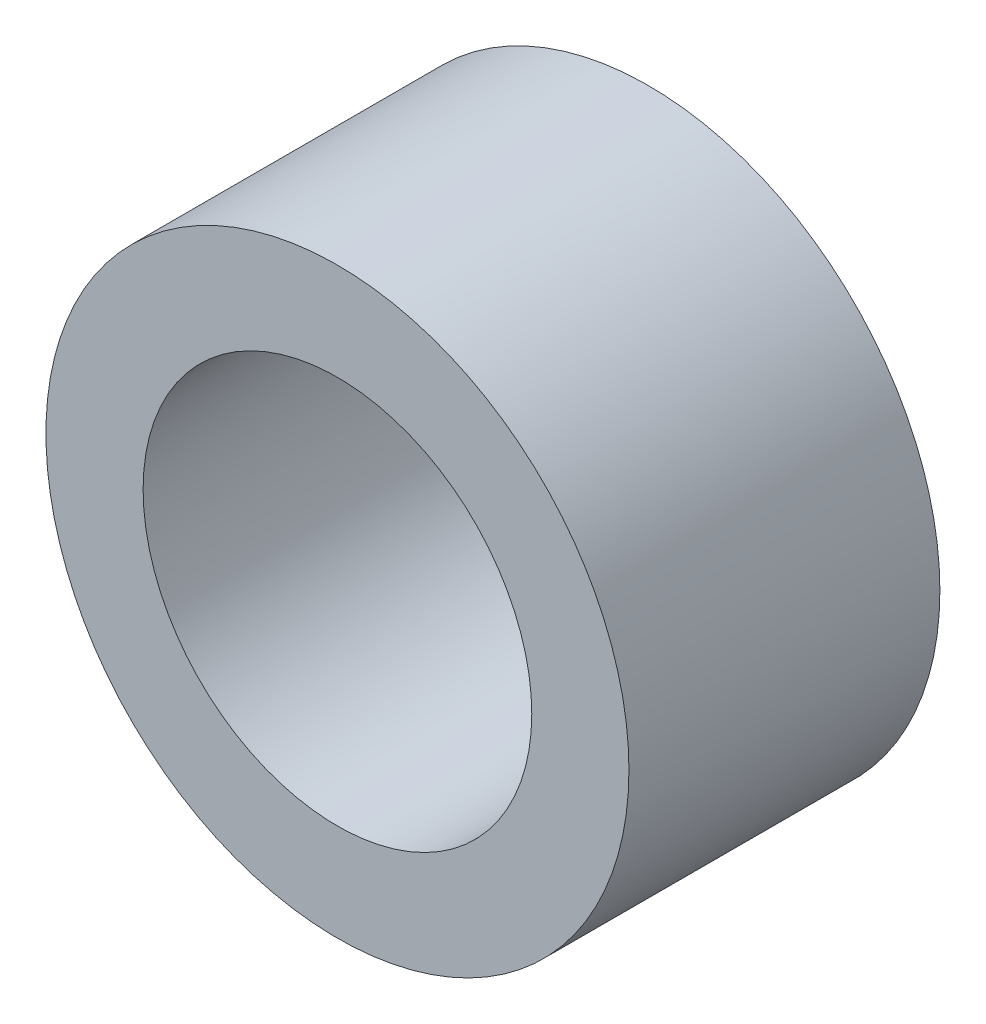
SolidWorks part; units mm, degrees
ref_plane "Front Plane" through (0, 0, 0) normal (0, 0, 1) x (1, 0, 0)
ref_plane "Top Plane" through (0, 0, 0) normal (0, 1, 0) x (1, 0, 0)
ref_plane "Right Plane" through (0, 0, 0) normal (1, 0, 0) x (0, 0, -1)
sketch "Sketch1" plane through (0, 0, 0) normal (0, 0, 1) x (1, 0, 0)
  circle A0 centre (0, 0) radius 30
  circle A1 centre (0, 0) radius 20
  dimension "D1" = 60
  dimension "D2" = 40
extrude "Boss-Extrude1" add sketch "Sketch1" along normal mid plane 32
